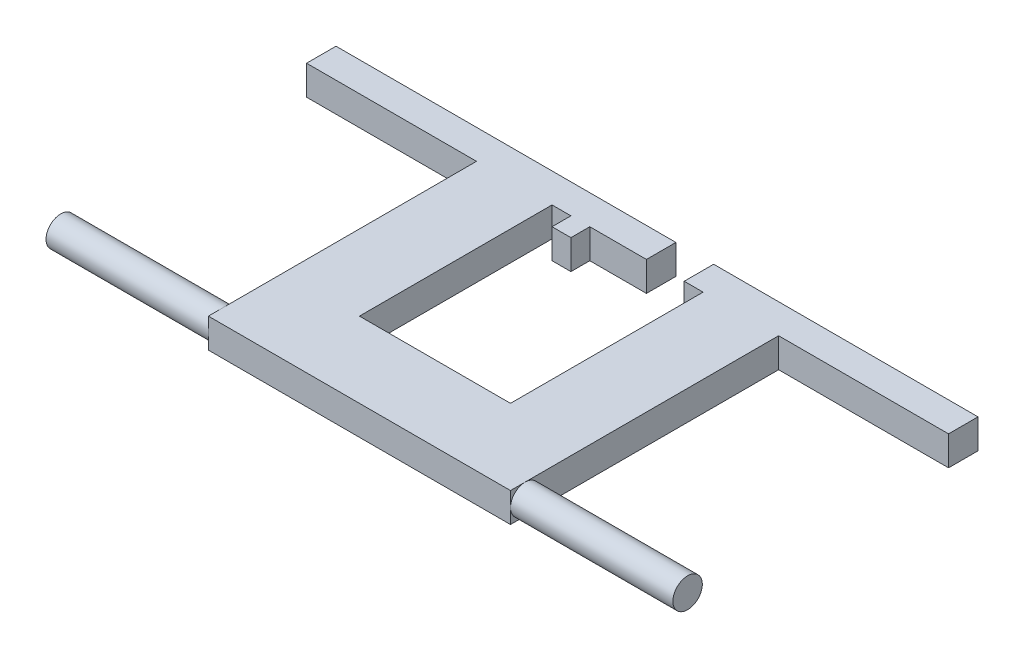
SolidWorks part; units mm, degrees
ref_plane "Front Plane" through (0, 0, 0) normal (0, 0, 1) x (1, 0, 0)
ref_plane "Top Plane" through (0, 0, 0) normal (0, 1, 0) x (1, 0, 0)
ref_plane "Right Plane" through (0, 0, 0) normal (1, 0, 0) x (0, 0, -1)
sketch "Sketch1" plane through (0, 0, 0) normal (0, 1, 0) x (1, 0, 0)
  line L1 (-75.2632, 13.0552) -> (94.7368, 13.0552)
  line L2 (-75.2632, 13.0552) -> (-75.2632, 5.2552)
  line L3 (-75.2632, 5.2552) -> (94.7368, 5.2552)
  line L4 (94.7368, 13.0552) -> (94.7368, 5.2552)
  dimension "D1" = 170
  dimension "D2" = 7.8
extrude "Boss-Extrude1" add sketch "Sketch1" along normal blind 7.8
sketch "Sketch2" plane through (0, 0, -5.2552) normal (0, 0, 1) x (1, 0, 0)
  line L0 (-75.2632, 7.8) -> (94.7368, 7.8) construction
  line L1 (-30.2632, 7.8) -> (-10.2632, 7.8)
  line L2 (-30.2632, 7.8) -> (-30.2632, 0)
  line L3 (-30.2632, 0) -> (-10.2632, 0)
  line L4 (-10.2632, 7.8) -> (-10.2632, 0)
  line L5 (43.34, 0) -> (-43.34, 0) construction
  line L6 (-75.2632, 7.8) -> (-75.2632, 0) construction
  dimension "D1" = 45
  dimension "D2" = 20
extrude "Boss-Extrude2" add sketch "Sketch2" along normal blind 71
sketch "Sketch3" plane through (-30.2632, 0, 0) normal (-1, 0, 0) x (0, 0, 1)
  line L0 (65.7448, 7.8) -> (65.7448, 0) construction
  line L1 (65.7448, 0) -> (-5.2552, 0) construction
  circle A0 centre (61.8448, 3.9) radius 3.9
  dimension "D1" = 7.8
  dimension "D2" = 3.9
  dimension "D3" = 3.9
extrude "Boss-Extrude3" add sketch "Sketch3" along normal blind 43
sketch "Sketch4" plane through (-10.2632, 0, 0) normal (1, 0, 0) x (0, 0, -1)
  line L0 (-65.7448, 0) -> (5.2552, 0) construction
  line L1 (-65.7448, 7.8) -> (-45.7448, 7.8)
  line L2 (-65.7448, 7.8) -> (-65.7448, 0)
  line L3 (-65.7448, 0) -> (-45.7448, 0)
  line L4 (-45.7448, 7.8) -> (-45.7448, 0)
  dimension "D1" = 20
extrude "Boss-Extrude4" add sketch "Sketch4" along normal blind 25
ref_plane "Plane1" through (9.7368, 0, 0) normal (-1, 0, 0) x (0, 0, 1)
mirror "Mirror1" about plane through (9.7368, 0, 0) normal (-1, 0, 0) of "Boss-Extrude3", "Boss-Extrude4", "Boss-Extrude2"
sketch "Sketch5" plane through (0, 0, -5.2552) normal (0, 0, 1) x (1, 0, 0)
  line L0 (-10.2632, 7.8) -> (29.7368, 7.8) construction
  line L1 (14.7368, 7.8) -> (24.7368, 7.8)
  line L2 (14.7368, 7.8) -> (14.7368, 0)
  line L3 (14.7368, 0) -> (24.7368, 0)
  line L4 (24.7368, 7.8) -> (24.7368, 0)
  line L5 (-10.2632, 0) -> (29.7368, 0) construction
  line L6 (29.7368, 0) -> (29.7368, 7.8) construction
  dimension "D1" = 5
  dimension "D2" = 10
extrude "Cut-Extrude1" cut sketch "Sketch5" against normal through all
sketch "Sketch6" plane through (0, 0, -5.2552) normal (0, 0, 1) x (1, 0, 0)
  line L0 (-10.2632, 7.8) -> (14.7368, 7.8) construction
  line L1 (-5.2632, 7.8) -> (-0.2632, 7.8)
  line L2 (-5.2632, 7.8) -> (-5.2632, 0)
  line L3 (-5.2632, 0) -> (-0.2632, 0)
  line L4 (-0.2632, 7.8) -> (-0.2632, 0)
  line L5 (-10.2632, 0) -> (14.7368, 0) construction
  line L7 (9.7368, 4.29) -> (9.7368, -4.29) construction
  dimension "D1" = 5
  dimension "D2" = 10
extrude "Boss-Extrude5" add sketch "Sketch6" along normal blind 5
